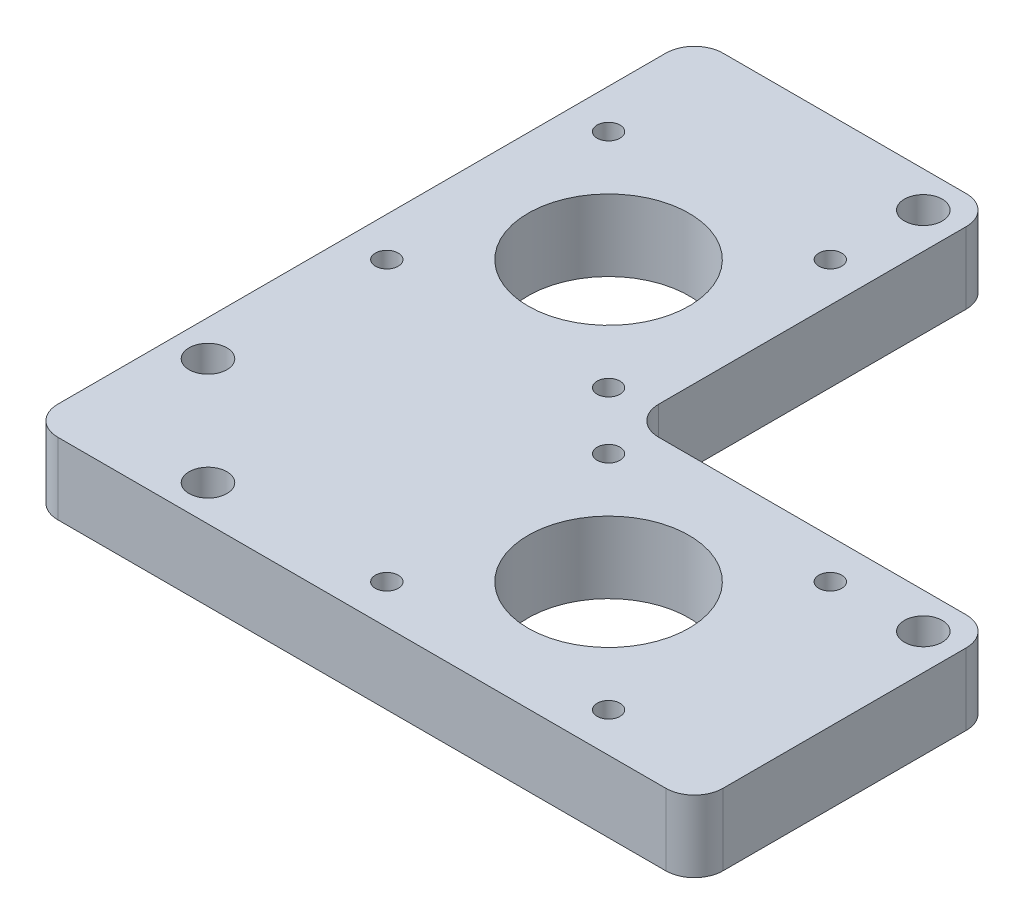
SolidWorks part; units mm, degrees
material "AISI 1045 Steel, cold drawn"
ref_plane "Front Plane" through (0, 0, 0) normal (0, 0, 1) x (1, 0, 0)
ref_plane "Top Plane" through (0, 0, 0) normal (0, 1, 0) x (1, 0, 0)
ref_plane "Right Plane" through (0, 0, 0) normal (1, 0, 0) x (0, 0, -1)
sketch "Sketch1" plane through (0, 0, 0) normal (0, 1, 0) x (1, 0, 0)
  line L1 (60, -21) -> (18, -21) construction
  line L2 (60, -21) -> (60, 21) construction
  line L3 (60, 21) -> (18, 21) construction
  line L4 (18, -21) -> (18, 21) construction
  line L5 (60, -21) -> (18, 21) construction
  line L6 (60, 21) -> (18, -21) construction
  line L7 (21, 18) -> (-21, 18) construction
  line L8 (21, 18) -> (21, 60) construction
  line L9 (21, 60) -> (-21, 60) construction
  line L10 (-21, 18) -> (-21, 60) construction
  line L11 (21, 18) -> (-21, 60) construction
  line L12 (21, 60) -> (-21, 18) construction
  line L14 (60, -21) -> (60, 21)
  line L15 (60, 21) -> (21, 21)
  line L16 (21, 21) -> (21, 60)
  line L17 (21, 60) -> (-21, 60)
  line L18 (-21, 60) -> (-21, 18)
  line L19 (-21, 18) -> (18, 18)
  line L20 (18, 18) -> (18, -21)
  line L21 (18, -21) -> (60, -21)
  point P0 (39, 0)
  point P5 (0, 39)
  dimension "D1" = 42
  dimension "D2" = 39
  dimension "D3" = 39
extrude "Boss-Extrude1" add sketch "Sketch1" along normal blind 10
hole_wizard "Ø22.5 (22.5) Diameter Hole1" positions "Sketch5" profile "Sketch7" hole size "Ø22.5" standard "ANSI Metric" end condition through all
sketch "Sketch5" plane through (0, 10, 0) normal (0, 1, 0) x (1, 0, 0)
  point P0 (0, 39)
  point P3 (39, 0)
sketch "Sketch7" plane through (0, 10, -39) normal (1, 0, 0) x (0, 0, 1)
  line L0 (0, 0) -> (0, 10)
  line L1 (0, 10) -> (11.25, 10)
  line L2 (11.25, 10) -> (11.25, 0)
  line L5 (11.25, 0) -> (0, 0)
  line L11 (0, -6.35) -> (0, 107.95) construction
  dimension "Thru Hole Dia." = 22.5
  dimension "Thru Hole Depth" = 10
sketch "Sketch8" plane through (0, 0, 0) normal (0, 1, 0) x (1, 0, 0)
  line L0 (21, 60) -> (-21, 18) construction
  line L1 (15.5, 23.5) -> (-15.5, 23.5)
  line L2 (15.5, 23.5) -> (15.5, 54.5)
  line L3 (15.5, 54.5) -> (-15.5, 54.5)
  line L4 (-15.5, 23.5) -> (-15.5, 54.5)
  line L5 (15.5, 23.5) -> (-15.5, 54.5) construction
  line L6 (15.5, 54.5) -> (-15.5, 23.5) construction
  line L7 (21, 18) -> (-21, 60) construction
  line L8 (60, 21) -> (18, -21) construction
  line L9 (23.5, -15.5) -> (54.5, -15.5)
  line L10 (23.5, -15.5) -> (23.5, 15.5)
  line L11 (23.5, 15.5) -> (54.5, 15.5)
  line L12 (54.5, -15.5) -> (54.5, 15.5)
  line L13 (23.5, -15.5) -> (54.5, 15.5) construction
  line L14 (23.5, 15.5) -> (54.5, -15.5) construction
  point P0 (0, 39)
  point P9 (39, 0)
  dimension "D1" = 31
hole_wizard "CBORE for M3 SHCS1" positions "Sketch9" profile "Sketch10" counterbore size "M3" standard "ANSI Metric" end condition through all
sketch "Sketch9" plane through (0, 0, 0) normal (0, -1, 0) x (-1, 0, 0)
  point P0 (-54.5, 15.5)
  point P3 (-23.5, 15.5)
  point P6 (-23.5, -15.5)
  point P9 (-54.5, -15.5)
  point P12 (-15.5, 54.5)
  point P15 (-15.5, 23.5)
  point P18 (15.5, 23.5)
  point P21 (15.5, 54.5)
sketch "Sketch10" plane through (54.5, 0, -15.5) normal (1, 0, 0) x (0, 0, -1)
  line L0 (0, 0) -> (0, 10)
  line L1 (0, 10) -> (1.6, 10)
  line L3 (1.6, 10) -> (1.6, 3)
  line L4 (1.6, 3) -> (3.25, 3)
  line L5 (3.25, 3) -> (3.25, 0)
  line L7 (3.25, 0) -> (0, 0)
  line L11 (0, -6.35) -> (0, 107.95) construction
  dimension "Thru Hole Dia." = 3.2
  dimension "Thru Hole Depth" = 10
  dimension "C'Bore Dia." = 6.5
  dimension "C'Bore Depth" = 3
sketch "Sketch16" plane through (0, 10, 0) normal (0, 1, 0) x (1, 0, 0)
  line L1 (17.1, 17.1) -> (-21, 17.1)
  line L2 (17.1, 17.1) -> (17.1, -21)
  line L6 (-21, 17.1) -> (-21, 18)
  line L7 (-21, 18) -> (18, 18)
  line L8 (18, 18) -> (18, -21)
  line L9 (18, -21) -> (17.1, -21)
  circle A0 centre (39, 0) radius 11.25 construction
  dimension "D1" = 21.9
extrude "Boss-Extrude2" add sketch "Sketch16" against normal up to surface (10 mm away) up to face at (54.5, 0, -18.75)
ref_plane "Plane1" through (0, 0, 0) normal (0.7071, 0, 0.7071) x (0.7071, 0, -0.7071)
sketch "Sketch17" plane through (0, 10, 0) normal (0, 1, 0) x (1, 0, 0)
  line L0 (17.1, -21) -> (60, -21) construction
  line L1 (60, 21) -> (72, 21)
  line L2 (60, 21) -> (60, -21)
  line L3 (60, -21) -> (72, -21)
  line L4 (72, 21) -> (72, -21)
  line L5 (60, -21) -> (60, 21) construction
  dimension "D1" = 12
extrude "Boss-Extrude3" add sketch "Sketch17" against normal up to surface (10 mm away) up to face at (54.5, 0, -18.75)
hole_wizard "M5 Clearance Hole1" positions "Sketch18" profile "Sketch19" hole size "M5" standard "ANSI Metric" end condition through all
sketch "Sketch18" plane through (0, 10, 0) normal (0, 1, 0) x (1, 0, 0)
  line L0 (72, 21) -> (21, 21) construction
  line L1 (72, -21) -> (72, 21) construction
  point P0 (67, 16)
  dimension "D1" = 5
  dimension "D2" = 5
sketch "Sketch19" plane through (67, 10, -16) normal (1, 0, 0) x (0, 0, 1)
  line L0 (0, 0) -> (0, 10)
  line L1 (0, 10) -> (2.65, 10)
  line L2 (2.65, 10) -> (2.65, 0)
  line L5 (2.65, 0) -> (0, 0)
  line L11 (0, -6.35) -> (0, 107.95) construction
  dimension "Thru Hole Dia." = 5.3
  dimension "Thru Hole Depth" = 10
mirror "Mirror1" about plane through (0, 0, 0) normal (0.7071, 0, 0.7071) of "Boss-Extrude3", "M5 Clearance Hole1"
sketch "Sketch20" plane through (0, 10, 0) normal (0, 1, 0) x (1, 0, 0)
  line L0 (-21, 72) -> (-21, 17.1) construction
  line L1 (-21, 17.1) -> (17.1, 17.1)
  line L2 (-21, 17.1) -> (-21, -21)
  line L3 (-21, -21) -> (17.1, -21)
  line L4 (17.1, 17.1) -> (17.1, -21)
  line L5 (-21, 17.1) -> (17.1, 17.1) construction
extrude "Boss-Extrude4" add sketch "Sketch20" against normal up to surface (10 mm away) up to face at (16, 0, -64.35)
hole_wizard "M5 Clearance Hole2" positions "Sketch21" profile "Sketch23" hole size "M5" standard "ANSI Metric" end condition through all
sketch "Sketch21" plane through (0, 10, 0) normal (0, 1, 0) x (1, 0, 0)
  line L0 (-21, -21) -> (72, -21) construction
  line L1 (-16, -1) -> (-1, -1) construction
  line L2 (-1, -1) -> (-1, -16) construction
  line L4 (-21, 72) -> (-21, -21) construction
  point P0 (-16, -1)
  point P2 (-1, -16)
  dimension "D1" = 5
  dimension "D2" = 20
  dimension "D3" = 20
sketch "Sketch23" plane through (-16, 10, 1) normal (1, 0, 0) x (0, 0, 1)
  line L0 (0, 0) -> (0, 10)
  line L1 (0, 10) -> (2.65, 10)
  line L2 (2.65, 10) -> (2.65, 0)
  line L5 (2.65, 0) -> (0, 0)
  line L11 (0, -6.35) -> (0, 107.95) construction
  dimension "Thru Hole Dia." = 5.3
  dimension "Thru Hole Depth" = 10
fillet "Fillet6" radius 4 6 edges at (72, 5, 21) (72, 5, -21) (21, 5, -21) (21, 5, -72) (-21, 5, -72) (-21, 5, 21)
